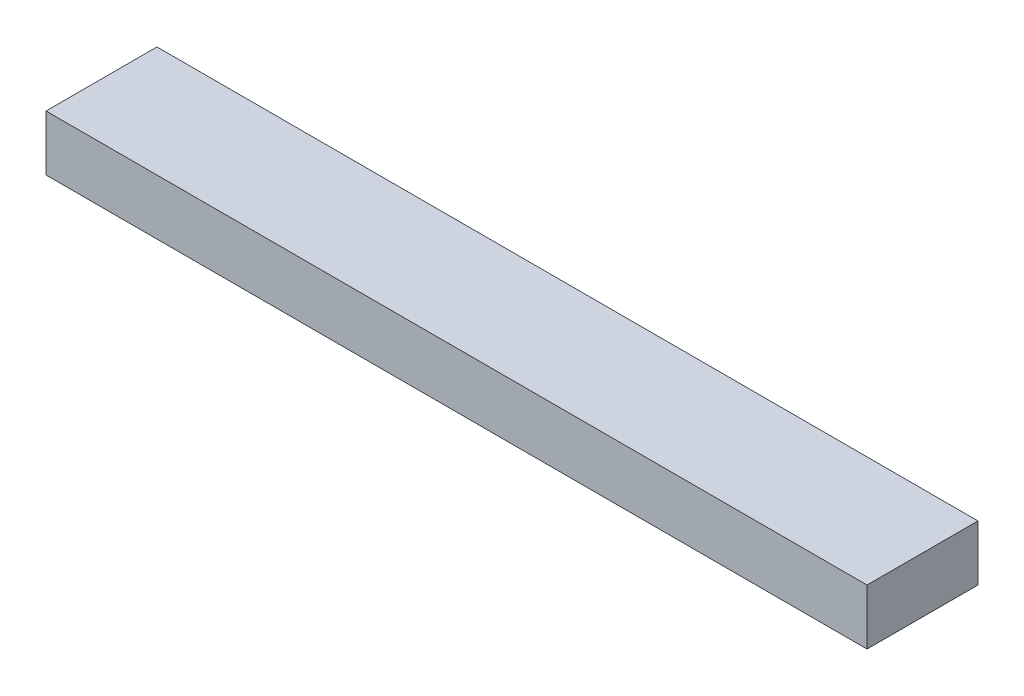
SolidWorks part; units mm, degrees
ref_plane "Front Plane" through (0, 0, 0) normal (0, 0, 1) x (1, 0, 0)
ref_plane "Top Plane" through (0, 0, 0) normal (0, 1, 0) x (1, 0, 0)
ref_plane "Right Plane" through (0, 0, 0) normal (1, 0, 0) x (0, 0, -1)
sketch "Sketch1" plane through (0, 0, 0) normal (0, 1, 0) x (1, 0, 0)
  line L1 (-23.495, -3.175) -> (23.495, -3.175)
  line L2 (-23.495, -3.175) -> (-23.495, 3.175)
  line L3 (-23.495, 3.175) -> (23.495, 3.175)
  line L4 (23.495, -3.175) -> (23.495, 3.175)
  line L5 (-23.495, -3.175) -> (23.495, 3.175) construction
  line L6 (-23.495, 3.175) -> (23.495, -3.175) construction
  point P0 (0, 0)
  dimension "D1" = 46.99
  dimension "D2" = 6.35
extrude "Boss-Extrude1" add sketch "Sketch1" along normal blind 3.175
